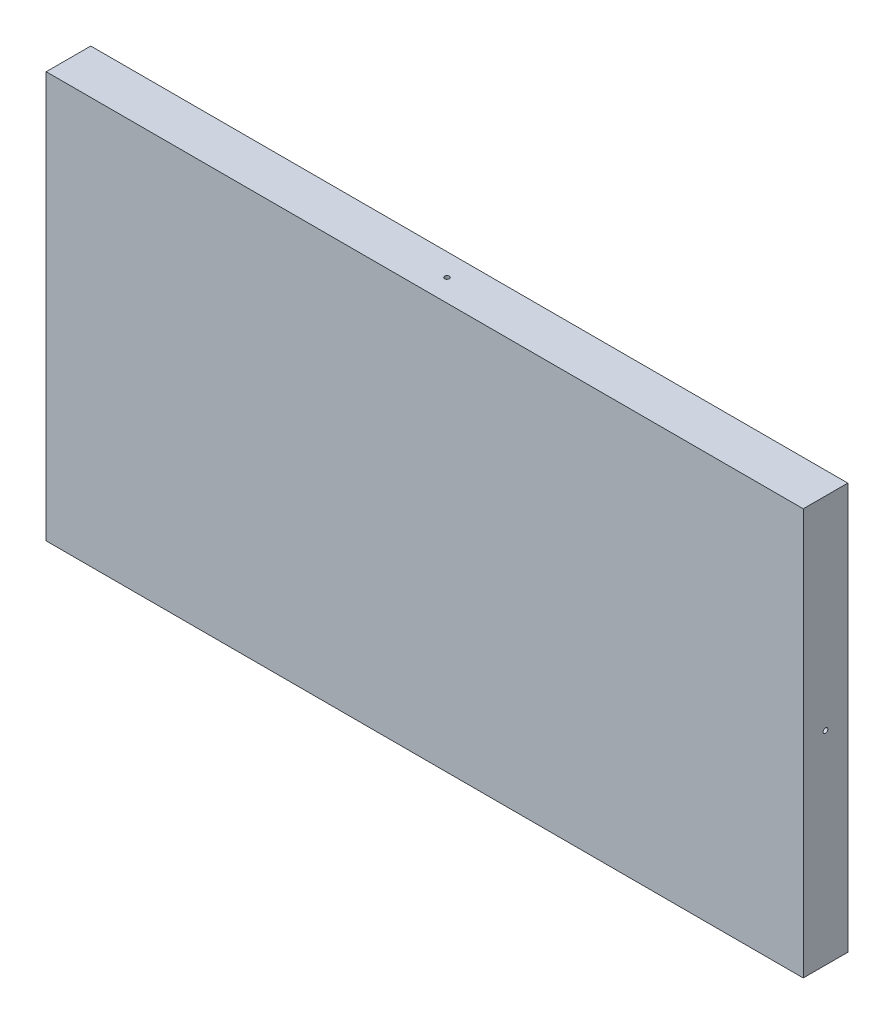
SolidWorks part; units mm, degrees
material "1.4511 (X3CrNb17)"
ref_plane "前视基准面" through (0, 0, 0) normal (0, 0, 1) x (1, 0, 0)
ref_plane "上视基准面" through (0, 0, 0) normal (0, 1, 0) x (1, 0, 0)
ref_plane "右视基准面" through (0, 0, 0) normal (1, 0, 0) x (0, 0, -1)
sketch "草图1" plane through (0, 0, 0) normal (0, 0, 1) x (1, 0, 0)
  line L1 (-340, 182.5) -> (340, 182.5)
  line L2 (-340, 182.5) -> (-340, -182.5)
  line L3 (-340, -182.5) -> (340, -182.5)
  line L4 (340, 182.5) -> (340, -182.5)
  line L5 (-340, 182.5) -> (340, -182.5) construction
  line L6 (-340, -182.5) -> (340, 182.5) construction
  point P0 (0, 0)
  dimension "D1" = 680
  dimension "D2" = 365
extrude "凸台-拉伸1" add sketch "草图1" along normal blind 40
sketch "草图2" plane through (0, -182.5, 0) normal (0, -1, 0) x (1, 0, 0)
  line L0 (-340, 40) -> (-340, 0) construction
  point P0 (0, 20)
  dimension "D1" = 340
hole_wizard "M5 螺纹孔1" positions "草图3" profile "草图4" tap size "M5" standard "GB" end condition through all
sketch "草图3" plane through (0, -182.5, 0) normal (0, -1, 0) x (-1, 0, 0)
  point P0 (0, -20)
sketch "草图4" plane through (0, -182.5, 20) normal (1, 0, 0) x (0, 0, -1)
  line L0 (0, 0) -> (0, 365)
  line L1 (0, 365) -> (2.1, 365)
  line L2 (2.1, 365) -> (2.1, 0)
  line L5 (2.1, 0) -> (0, 0)
  line L11 (0, -6.35) -> (0, 107.95) construction
  dimension "通孔螺纹孔钻头直径" = 4.2
  dimension "通孔螺纹孔钻头深度" = 365
cosmetic thread "孔螺蚊线1"
sketch "草图6" plane through (-340, 0, 0) normal (-1, 0, 0) x (0, 0, 1)
  line L0 (40, 182.5) -> (0, 182.5) construction
  point P0 (20, 0)
  dimension "D1" = 182.5
hole_wizard "M5 螺纹孔2" positions "草图7" profile "草图8" tap size "M5" standard "GB" end condition through all
sketch "草图7" plane through (-340, 0, 0) normal (-1, 0, 0) x (0, 0, 1)
  point P0 (20, 0)
sketch "草图8" plane through (-340, 0, 20) normal (0, 1, 0) x (0, 0, 1)
  line L0 (0, 0) -> (0, 680)
  line L1 (0, 680) -> (2.1, 680)
  line L2 (2.1, 680) -> (2.1, 0)
  line L5 (2.1, 0) -> (0, 0)
  line L11 (0, -6.35) -> (0, 107.95) construction
  dimension "通孔螺纹孔钻头直径" = 4.2
  dimension "通孔螺纹孔钻头深度" = 680
cosmetic thread "孔螺蚊线2"
